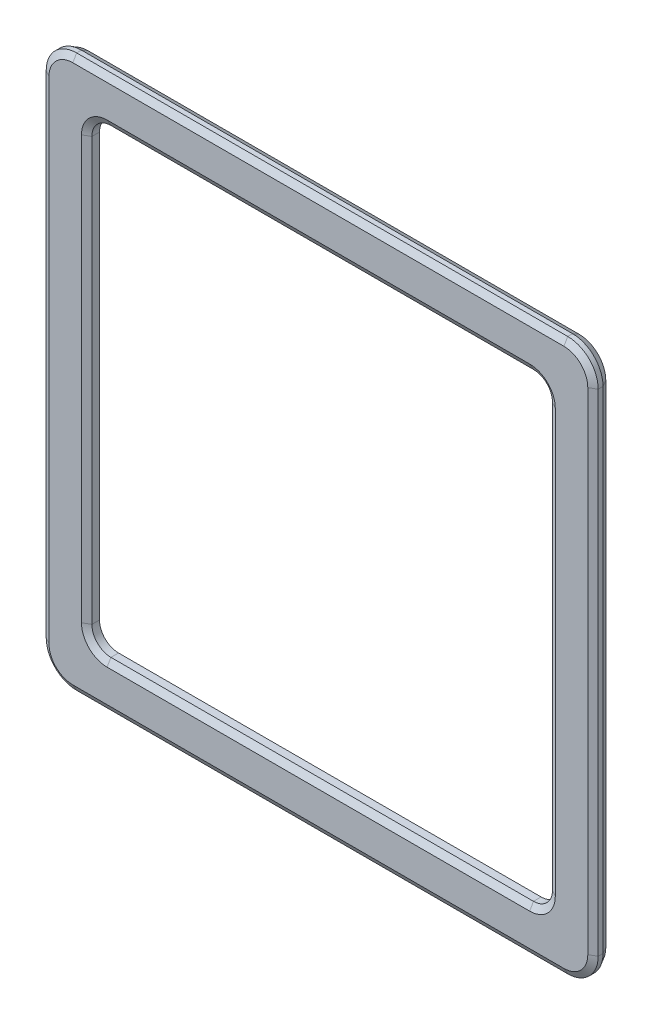
SolidWorks part; units mm, degrees
ref_plane "Front" through (0, 0, 0) normal (0, 0, 1) x (1, 0, 0)
ref_plane "Top" through (0, 0, 0) normal (0, 1, 0) x (1, 0, 0)
ref_plane "Right" through (0, 0, 0) normal (1, 0, 0) x (0, 0, -1)
sketch "Esquisse1" plane through (0, 0, 0) normal (0, 0, 1) x (1, 0, 0)
  line L0 (72.5, 0) -> (72.5, 12) construction
  line L1 (0, 0) -> (145, 0)
  line L2 (0, 0) -> (0, 145)
  line L3 (0, 145) -> (145, 145)
  line L4 (145, 0) -> (145, 145)
  line L5 (0, 72.5) -> (12, 72.5) construction
  line L6 (133, 12) -> (12, 12)
  line L7 (12, 12) -> (12, 133)
  line L8 (12, 133) -> (133, 133)
  line L9 (133, 133) -> (133, 12)
  dimension "D1" = 145
  dimension "D2" = 145
  dimension "D3" = 121
  dimension "D4" = 121
extrude "Boss.-Extru.1" add sketch "Esquisse1" along normal blind 4
fillet "Congé3" radius 8 4 edges at (145, 145, 2) (0, 145, 2) (0, 0, 2) (145, 0, 2)
fillet "Congé4" radius 5 4 edges at (133, 12, 2) (133, 133, 2) (12, 133, 2) (12, 12, 2)
chamfer "Chanfrein1" distance 1 angle 60 32 edges at (133, 72.5, 0) (131.5355, 131.5355, 0) (131.5355, 13.4645, 0) (72.5, 133, 0) (72.5, 12, 0) (13.4645, 131.5355, 0) (13.4645, 13.4645, 0) (12, 72.5, 0) (72.5, 0, 0) (142.6569, 2.3431, 0) (2.3431, 2.3431, 0) (145, 72.5, 0) (0, 72.5, 0) (142.6569, 142.6569, 0) (2.3431, 142.6569, 0) (72.5, 145, 0) (13.4645, 131.5355, 4) (12, 72.5, 4) (13.4645, 13.4645, 4) (72.5, 12, 4) (131.5355, 13.4645, 4) (133, 72.5, 4) (131.5355, 131.5355, 4) (72.5, 133, 4) (142.6569, 2.3431, 4) (72.5, 0, 4) (2.3431, 2.3431, 4) (0, 72.5, 4) (2.3431, 142.6569, 4) (72.5, 145, 4) (142.6569, 142.6569, 4) (145, 72.5, 4)
